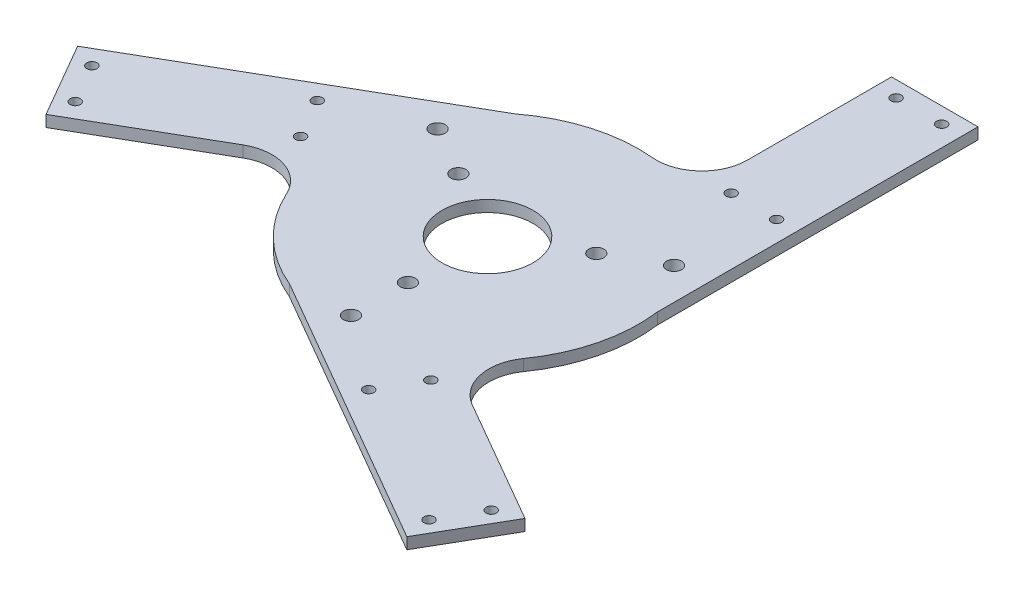
SolidWorks part; units mm, degrees
ref_plane "정면" through (0, 0, 0) normal (0, 0, 1) x (1, 0, 0)
ref_plane "윗면" through (0, 0, 0) normal (0, 1, 0) x (1, 0, 0)
ref_plane "우측면" through (0, 0, 0) normal (1, 0, 0) x (0, 0, -1)
sketch "스케치16" plane through (0, 0, 0) normal (0, 1, 0) x (1, 0, 0)
  line L0 (0, 100) -> (28.01, 100)
  line L3 (28.01, 88.75) -> (62.01, 88.75)
  line L8 (28.01, 88.75) -> (28.01, 135.25)
  line L9 (28.01, 135.25) -> (62.01, 135.25)
  line L10 (62.01, 88.75) -> (62.01, 135.25)
  circle A0 centre (0, 0) radius 100
  circle A3 centre (28.01, 100) radius 10.25
  dimension "D1" = 200
  dimension "D2" = 28.01
  dimension "D3" = 20.5
  dimension "D4" = 11.25
  dimension "D5" = 46.5
  dimension "D6" = 34
sketch "스케치2" plane through (0, 0, 0) normal (0, 1, 0) x (1, 0, 0)
  line L0 (28.01, 60.3969) -> (28.01, 149.5382)
  line L1 (28.01, 149.5382) -> (66.01, 149.5382)
  line L2 (66.01, 149.5382) -> (66.01, 8.662)
  line L3 (38.3003, -54.4558) -> (115.4989, -99.0265)
  line L4 (115.4989, -99.0265) -> (96.4989, -131.9354)
  line L5 (96.4989, -131.9354) -> (-25.5035, -61.4974)
  line L6 (-66.3103, -5.9411) -> (-143.5089, -50.5117)
  line L7 (-143.5089, -50.5117) -> (-162.5089, -17.6028)
  line L8 (-162.5089, -17.6028) -> (-40.5065, 52.8353)
  line L27 (-66.3103, -5.9411) -> (-143.5089, -50.5117) [skipped]
  line L28 (-143.5089, -50.5117) -> (-162.5089, -17.6028) [skipped]
  line L29 (-162.5089, -17.6028) -> (-40.5065, 52.8353) [skipped]
  line L30 (38.3003, -54.4558) -> (115.4989, -99.0265) [skipped]
  line L31 (115.4989, -99.0265) -> (96.4989, -131.9354) [skipped]
  line L32 (96.4989, -131.9354) -> (-25.5035, -61.4974) [skipped]
  circle A0 centre (0, 0) radius 66.5759
  arc A2 (54.3293, -38.4795) -> (60.6503, -67.3597) centre (70.6503, -50.0391) ccw
  arc A3 (6.1596, 66.2903) -> (28.01, 86.2046) centre (8.01, 86.2046) ccw
  arc A4 (-60.4889, -27.8108) -> (-88.6603, -18.8449) centre (-78.6603, -36.1654) ccw
  arc A11 (-60.4889, -27.8108) -> (-88.6603, -18.8449) centre (-78.6603, -36.1654) ccw [skipped]
  arc A12 (54.3293, -38.4795) -> (60.6503, -67.3597) centre (70.6503, -50.0391) ccw [skipped]
  point P9 (0, 0)
  point P10 (0, 0)
  point P13 (-0.0068, -0.0003)
  point P16 (0.0037, -0.0058)
  point P18 (0.0037, -0.0058)
  point P19 (0.0032, 0.0061)
  point P20 (0, 0)
  point P26 (0.0032, 0.0061)
  point P28 (-0.0068, -0.0003)
  point P30 (0, 0)
  point P32 (0.0032, 0.0061)
  point P36 (-0.0068, -0.0003)
  point P37 (0.0037, -0.0058)
  point P38 (0, 0)
  point P39 (0, 0)
  point P40 (0, 0)
  point P41 (0, 0)
  point P42 (0, 0)
  point P43 (0, 0)
  point P44 (0, 0)
  dimension "D8" = 38
  dimension "D10" = 20
  dimension "D2" = 3
  dimension "D3" = 3
extrude "보스-돌출1" add sketch "스케치2" against normal blind 5
sketch "스케치3" plane through (0, -5, 0) normal (0, -1, 0) x (-1, 0, 0)
  circle A0 centre (0, 0) radius 20
  dimension "D1" = 40
extrude "컷-돌출1" cut sketch "스케치3" against normal through all
hole_wizard "M6 여유 구멍1" positions "스케치6" profile "스케치7" hole size "M6" standard "ISO" end condition through all
sketch "스케치6" plane through (0, -5, 0) normal (0, -1, 0) x (-1, 0, 0)
  line L0 (0, 0) -> (0, -60) construction
  point P2 (0, -60)
  point P8 (0, -35)
  point P19 (-51.9615, 30)
  point P20 (-30.3109, 17.5)
  point P21 (51.9615, 30)
  point P22 (30.3109, 17.5)
  dimension "D1" = 60
  dimension "D2" = 35
  dimension "D3" = 3
sketch "스케치7" plane through (-30.3109, -5, -17.5) normal (1, 0, 0) x (0, 0, -1)
  line L0 (0, 0) -> (0, 5)
  line L1 (0, 5) -> (3.3, 5)
  line L2 (3.3, 5) -> (3.3, 0)
  line L5 (3.3, 0) -> (0, 0)
  line L11 (0, -6.35) -> (0, 107.95) construction
  dimension "관통 구멍 지름" = 6.6
  dimension "관통 구멍 깊이" = 5
hole_wizard "M4 여유 구멍2" positions "스케치17" profile "스케치18" hole size "M4" standard "ISO"
sketch "스케치17" plane through (0, 0, 0) normal (0, 1, 0) x (1, 0, 0)
  line L0 (47.01, 169.6957) -> (47.01, 127.641) construction
  line L2 (66.01, 149.5382) -> (66.01, 8.662) construction
  line L3 (28.01, 149.5382) -> (66.01, 149.5382) construction
  line L4 (57.7898, 106.2882) -> (90.146, 106.2882) construction
  point P2 (57.01, 142.5382)
  point P18 (37.01, 142.5382)
  point P19 (37.01, 70.0382)
  point P20 (57.01, 70.0382)
  point P152 (94.9367, -120.6412)
  point P153 (104.9367, -103.3207)
  point P154 (42.1499, -67.0707)
  point P155 (32.1499, -84.3912)
  point P156 (-151.9467, -21.897)
  point P157 (-141.9467, -39.2175)
  point P158 (-79.1599, -2.9675)
  point P159 (-89.1599, 14.353)
  dimension "D1" = 19
  dimension "D2" = 10
  dimension "D3" = 7
  dimension "D4" = 72.5
sketch "스케치18" plane through (57.01, 0, -142.5382) normal (1, 0, 0) x (0, 0, 1)
  line L0 (0, 0) -> (0, 11.3519)
  line L1 (0, 11.3519) -> (2.25, 10)
  line L2 (2.25, 10) -> (2.25, 0)
  line L5 (2.25, 0) -> (0, 0)
  line L10 (0, 11.3519) -> (-2.25, 10) construction
  line L11 (0, -6.35) -> (0, 107.95) construction
  dimension "구멍 지름" = 4.5
  dimension "구멍 깊이" = 10
  dimension "드릴 각도" = 118
